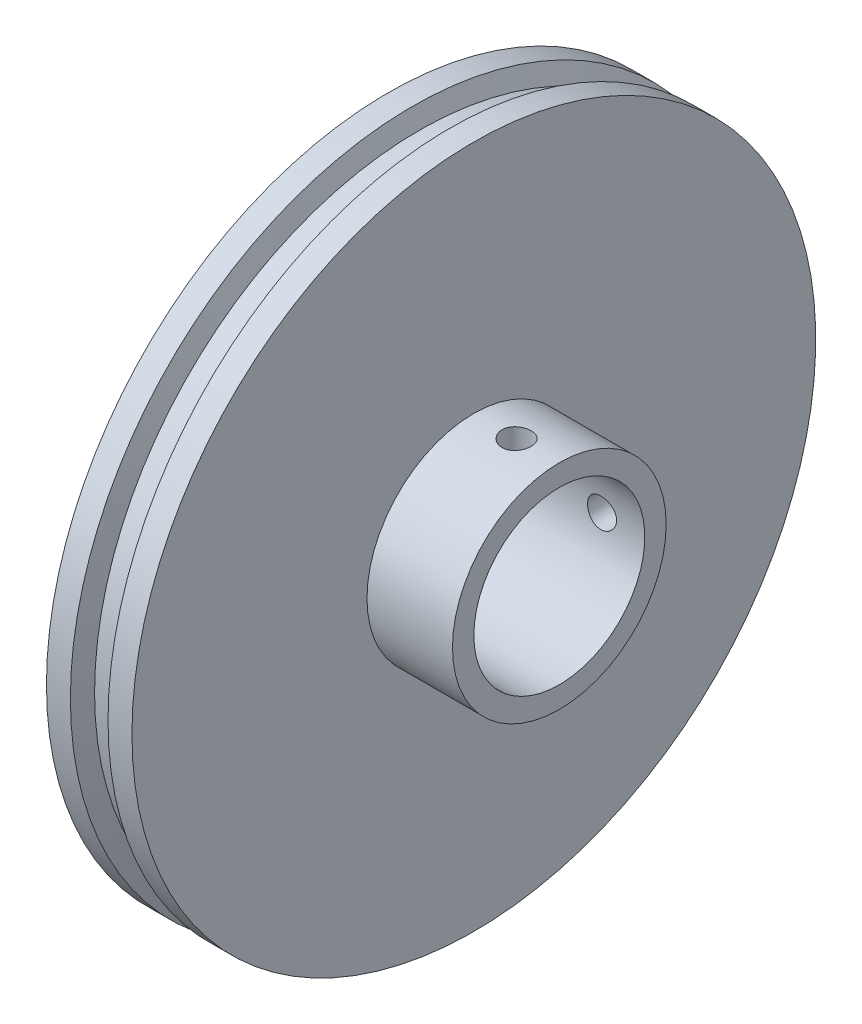
SolidWorks part; units mm, degrees
ref_plane "前视基准面" through (0, 0, 0) normal (0, 0, 1) x (1, 0, 0)
ref_plane "上视基准面" through (0, 0, 0) normal (0, 1, 0) x (1, 0, 0)
ref_plane "右视基准面" through (0, 0, 0) normal (1, 0, 0) x (0, 0, -1)
sketch "草图1" plane through (0, 0, 0) normal (0, 0, 1) x (1, 0, 0)
  line L0 (-5, 0) -> (15, 0) construction
  line L1 (0, 40) -> (0, -40) construction
  line L2 (0, 38) -> (1.3716, 38)
  line L3 (1.3716, 38) -> (2.2, 40)
  line L4 (2.2, 40) -> (5, 40)
  line L5 (5, 40) -> (5, 12.5)
  line L6 (5, 12.5) -> (15, 12.5)
  line L7 (15, 12.5) -> (15, 10)
  line L8 (15, 10) -> (0, 10)
  line L9 (-2.2, 40) -> (2.2, 40) construction
  line L10 (-5, 0) -> (-5, 40) construction
  line L11 (10, 12.5) -> (10, 10) construction
  point P18 (12, 12.5)
  dimension "D1" = 80
  dimension "T" = 10
  dimension "D2" = 76
  dimension "PD" = 80
  dimension "D3" = 22.5
  dimension "(d)" = 20
  dimension "L" = 20
  dimension "e" = 5
  dimension "M" = 4
  dimension "D" = 25
  dimension "W" = 4.4
sketch "草图2" plane through (0, 0, 0) normal (1, 0, 0) x (0, 0, -1)
  line L0 (-1.5, 9.8869) -> (-1.5, 11.4)
  line L1 (-1.5, 11.4) -> (1.5, 11.4)
  line L2 (1.5, 11.4) -> (1.5, 9.8869)
  line L3 (0, 0) -> (0, 10) construction
  line L4 (0, 0) -> (0, 40) construction
  circle A0 centre (0, 0) radius 10
  dimension "b" = 3
  dimension "t" = 1.4
sketch "草图3" [suppressed] plane through (0, 0, 0) normal (0, 0, 1) x (1, 0, 0)
  line L0 (5, 11) -> (5, 8) construction
  line L1 (2.0642, 11) -> (5, 11) construction
  line L2 (1.0287, 8.5) -> (2.0642, 11) construction
  line L3 (0, 8.5) -> (1.0287, 8.5) construction
  line L4 (5, 11) -> (5, 2)
  line L5 (2.0642, 11) -> (5, 11)
  line L6 (1.0287, 8.5) -> (2.0642, 11)
  line L7 (-1.0287, 8.5) -> (1.0287, 8.5)
  line L8 (11, 2) -> (0, 2) construction
  line L9 (5, 2) -> (-5, 2)
  line L10 (0, 11) -> (0, 0) construction
  line L11 (-1.0287, 8.5) -> (-2.0642, 11)
  line L12 (-2.0642, 11) -> (-5, 11)
  line L13 (-5, 11) -> (-5, 2)
revolve "旋转1" [suppressed] add sketch "草图3" angle 360 about L0
sketch "草图4" [suppressed] plane through (0, 0, 0) normal (0, 0, 1) x (1, 0, 0)
  line L0 (1.275, 0) -> (1.275, 8)
  line L2 (1.275, 8) -> (1.7, 8)
  line L3 (1.7, 8) -> (1.7, 11)
  line L4 (1.7, 11) -> (0, 11)
  line L5 (0, 11) -> (0, 0)
  line L6 (0, 0) -> (1.275, 0)
  line L7 (11, 2) -> (0, 2) construction
  dimension "D1" = 1.275
  dimension "D2" = 1.7
  dimension "D3" = 6
revolve "切除-旋转2" [suppressed] cut sketch "草图4" angle 360 about L1
cosmetic thread "装饰螺纹线1" [suppressed] parameters "D2"=3
pattern_circular "阵列(圆周)1" [suppressed] count 2 every 90
sketch "草图5" [suppressed] plane through (0, 0, 0) normal (1, 0, 0) x (0, 0, -1)
  line L0 (-1.5, 1.3229) -> (-1.5, 3.4) construction
  line L1 (-1.5, 3.4) -> (1.5, 3.4) construction
  line L2 (1.5, 3.4) -> (1.5, 1.3229) construction
  line L3 (-1.5, 1.3229) -> (-1.5, 3.4)
  line L4 (-1.5, 3.4) -> (1.5, 3.4)
  line L5 (1.5, 3.4) -> (1.5, 1.3229)
  circle A0 centre (0, 0) radius 2 construction
  arc A1 (1.5, 1.3229) -> (-1.5, 1.3229) centre (0, 0) ccw
extrude "切除-拉伸1" [suppressed] cut sketch "草图5" against normal through all and the other way through all
sketch "草图6" plane through (0, 0, 0) normal (0, 0, 1) x (1, 0, 0)
  line L0 (15, 12.5) -> (15, 10) construction
  line L1 (5, 12.5) -> (15, 12.5) construction
  line L2 (5, 40) -> (5, 12.5) construction
  line L3 (2.2, 40) -> (5, 40) construction
  line L4 (1.3716, 38) -> (2.2, 40) construction
  line L5 (0, 38) -> (1.3716, 38) construction
  line L7 (15, 12.5) -> (15, 10)
  line L8 (5, 12.5) -> (15, 12.5)
  line L9 (5, 40) -> (5, 12.5)
  line L10 (2.2, 40) -> (5, 40)
  line L11 (1.3716, 38) -> (2.2, 40)
  line L12 (-1.3716, 38) -> (1.3716, 38)
  line L13 (15, 10) -> (-5, 10)
  line L14 (0, 0) -> (0, 40) construction
  line L15 (-1.3716, 38) -> (-2.2, 40)
  line L16 (-2.2, 40) -> (-5, 40)
  line L17 (-5, 40) -> (-5, 10)
  line L19 (-5, 0) -> (-5, 40) construction
revolve "旋转2" add sketch "草图6" angle 360 about L0
sketch "草图7" plane through (0, 0, 0) normal (0, 0, 1) x (1, 0, 0)
  line L0 (10, 40) -> (10, 0)
  line L1 (10, 0) -> (11.7, 0)
  line L2 (11.7, 0) -> (11.7, 40)
  line L3 (11.7, 40) -> (10, 40)
  line L4 (-5, 0) -> (15, 0) construction
  dimension "D1" = 1.7
revolve "切除-旋转3" cut sketch "草图7" angle 360 about L0
cosmetic thread "装饰螺纹线2" parameters "D2"=4
pattern_circular "阵列(圆周)2" count 2 every 90 about axis through (-5, 0, 0) along (-1, 0, 0) of "切除-旋转3"
sketch "草图8" [suppressed] plane through (0, 0, 0) normal (1, 0, 0) x (0, 0, -1)
  line L0 (-1.5, 1.3229) -> (-1.5, 3.4) construction
  line L1 (-1.5, 3.4) -> (1.5, 3.4) construction
  line L2 (1.5, 3.4) -> (1.5, 1.3229) construction
  line L3 (-1.5, 1.3229) -> (-1.5, 3.4)
  line L4 (-1.5, 3.4) -> (1.5, 3.4)
  line L5 (1.5, 3.4) -> (1.5, 1.3229)
  circle A0 centre (0, 0) radius 2 construction
  arc A1 (1.5, 1.3229) -> (-1.5, 1.3229) centre (0, 0) ccw
extrude "切除-拉伸2" [suppressed] cut sketch "草图8" against normal through all and the other way through all
sketch "草图9" [suppressed] plane through (0, 0, 0) normal (0, 0, 1) x (1, 0, 0)
  line L1 (2.0642, 11) -> (5, 11) construction
  line L2 (5, 11) -> (5, 2)
  line L3 (2.3094, 11) -> (5, 11)
  line L4 (0, 11) -> (0, -11) construction
  line L5 (-1.65, 10) -> (1.65, 10) construction
  line L6 (1.299, 9.25) -> (2.3094, 11)
  line L7 (0, 11) -> (0, 0) construction
  line L8 (11, 2) -> (0, 2) construction
  line L9 (-2.3094, 11) -> (-5, 11)
  line L10 (-1.299, 9.25) -> (-2.3094, 11)
  line L11 (5, 2) -> (-5, 2)
  line L12 (-5, 0) -> (-5, 11) construction
  line L13 (-5, 2) -> (-5, 11)
  arc A0 (-1.299, 9.25) -> (1.299, 9.25) centre (0, 10) ccw
  dimension "D1" = 30
revolve "旋转3" [suppressed] add sketch "草图9" angle 360 about L0
sketch "草图10" [suppressed] plane through (0, 0, 0) normal (0, 0, 1) x (1, 0, 0)
  line L0 (1.7, 11) -> (1.7, 8)
  line L1 (1.7, 8) -> (1.275, 8)
  line L2 (1.275, 8) -> (1.275, 0)
  line L3 (-5, 0) -> (11, 0) construction
  line L4 (1.275, 0) -> (0, 0)
  line L5 (0, 0) -> (0, 11)
  line L6 (0, 11) -> (1.7, 11)
  line L7 (11, 2) -> (0, 2) construction
  dimension "D1" = 1.275
  dimension "D2" = 1.7
  dimension "D3" = 6
revolve "切除-旋转4" [suppressed] cut sketch "草图10" angle 360 about L1
cosmetic thread "装饰螺纹线3" [suppressed] parameters "D2"=3
pattern_circular "阵列(圆周)3" [suppressed] count 2 every 90
sketch "草图11" [suppressed] plane through (0, 0, 0) normal (1, 0, 0) x (0, 0, -1)
  line L0 (-1.5, 1.3229) -> (-1.5, 3.4) construction
  line L1 (-1.5, 3.4) -> (1.5, 3.4) construction
  line L2 (1.5, 3.4) -> (1.5, 1.3229) construction
  line L3 (-1.5, 1.3229) -> (-1.5, 3.4)
  line L4 (-1.5, 3.4) -> (1.5, 3.4)
  line L5 (1.5, 3.4) -> (1.5, 1.3229)
  circle A0 centre (0, 0) radius 2 construction
  arc A1 (1.5, 1.3229) -> (-1.5, 1.3229) centre (0, 0) ccw
extrude "切除-拉伸3" [suppressed] cut sketch "草图11" against normal through all and the other way through all
sketch "草图12" [suppressed] plane through (0, 0, 0) normal (0, 0, 1) x (1, 0, 0)
  line L0 (2.0642, 11) -> (5, 11) construction
  line L1 (2.3094, 11) -> (5, 11)
  line L2 (-1.65, 10) -> (1.65, 10) construction
  line L3 (1.299, 9.25) -> (2.3094, 11)
  line L4 (0, 11) -> (0, -11) construction
  line L5 (0, 11) -> (0, 0) construction
  line L6 (-2.3094, 11) -> (-5, 11)
  line L7 (-1.299, 9.25) -> (-2.3094, 11)
  line L8 (5, 11) -> (5, 8)
  line L9 (5, 8) -> (11, 8)
  line L10 (11, 8) -> (11, 2)
  line L11 (11, 2) -> (-5, 2)
  line L12 (-5, 0) -> (-5, 11) construction
  line L13 (-5, 2) -> (-5, 11)
  arc A0 (-1.299, 9.25) -> (1.299, 9.25) centre (0, 10) ccw
  dimension "D1" = 30
revolve "旋转4" [suppressed] add sketch "草图12" angle 360 about L0
sketch "草图13" [suppressed] plane through (0, 0, 0) normal (0, 0, 1) x (1, 0, 0)
  line L0 (8, 11) -> (8, 0)
  line L1 (-5, 0) -> (11, 0) construction
  line L2 (8, 0) -> (9.275, 0)
  line L4 (9.275, 0) -> (9.275, 11)
  line L5 (9.275, 11) -> (8, 11)
  dimension "D1" = 1.7
revolve "切除-旋转5" [suppressed] cut sketch "草图13" angle 360 about L0
cosmetic thread "装饰螺纹线4" [suppressed] parameters "D2"=4
pattern_circular "阵列(圆周)4" [suppressed] count 2 every 90
sketch "草图14" [suppressed] plane through (0, 0, 0) normal (1, 0, 0) x (0, 0, -1)
  line L0 (-1.5, 1.3229) -> (-1.5, 3.4) construction
  line L1 (-1.5, 3.4) -> (1.5, 3.4) construction
  line L2 (1.5, 3.4) -> (1.5, 1.3229) construction
  line L3 (-1.5, 1.3229) -> (-1.5, 3.4)
  line L4 (-1.5, 3.4) -> (1.5, 3.4)
  line L5 (1.5, 3.4) -> (1.5, 1.3229)
  circle A0 centre (0, 0) radius 2 construction
  arc A1 (1.5, 1.3229) -> (-1.5, 1.3229) centre (0, 0) ccw
extrude "切除-拉伸4" [suppressed] cut sketch "草图14" against normal through all and the other way through all
